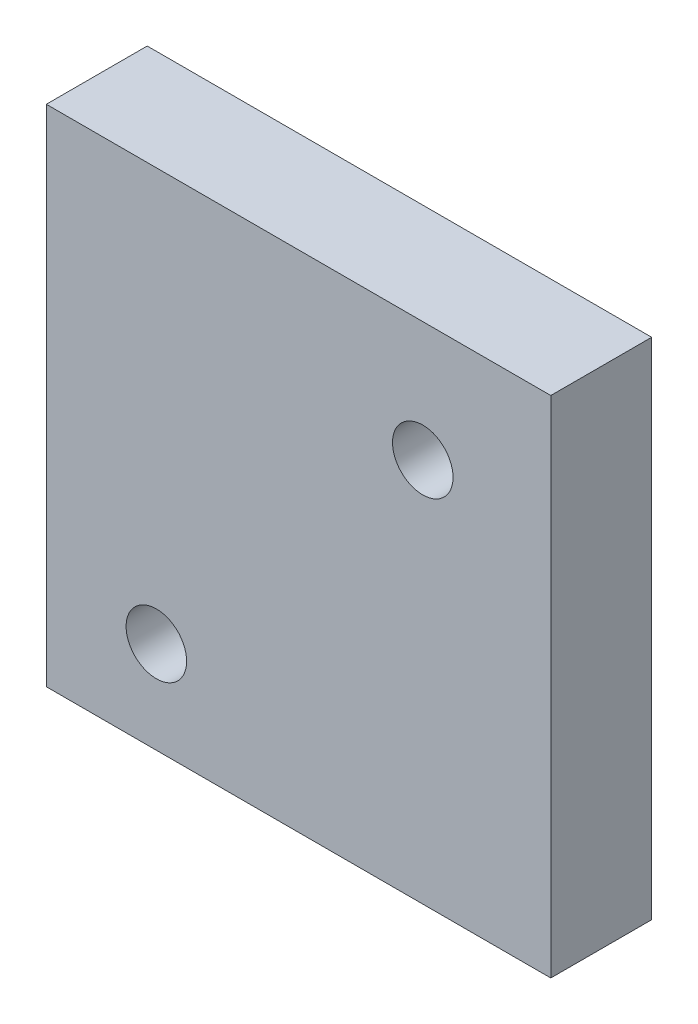
SolidWorks part; units mm, degrees
ref_plane "Front" through (0, 0, 0) normal (0, 0, 1) x (1, 0, 0)
ref_plane "Top" through (0, 0, 0) normal (0, 1, 0) x (1, 0, 0)
ref_plane "Right" through (0, 0, 0) normal (1, 0, 0) x (0, 0, -1)
sketch "草图1" plane through (0, 0, 0) normal (0, 0, 1) x (1, 0, 0)
  line L1 (0, 0) -> (100, 0)
  line L2 (0, 0) -> (0, 100)
  line L3 (0, 100) -> (100, 100)
  line L4 (100, 0) -> (100, 100)
  dimension "D1" = 100
  dimension "D2" = 100
extrude "凸台-拉伸1" add sketch "草图1" along normal blind 20
hole_wizard "Ø12.0 (12) 直径孔1" positions "草图2" profile "草图3" hole size "Ø12.0" standard "ISO" end condition through all
sketch "草图2" plane through (0, 0, 20) normal (0, 0, 1) x (1, 0, 0)
  point P0 (74.6237, 76.2464)
  point P2 (21.8121, 18.2761)
sketch "草图3" plane through (74.6237, 76.2464, 20) normal (1, 0, 0) x (0, -1, 0)
  line L0 (0, 0) -> (0, 20)
  line L1 (0, 20) -> (6, 20)
  line L2 (6, 20) -> (6, 0)
  line L5 (6, 0) -> (0, 0)
  line L11 (0, -6.35) -> (0, 107.95) construction
  dimension "通孔孔直径" = 12
  dimension "通孔孔深度" = 20
